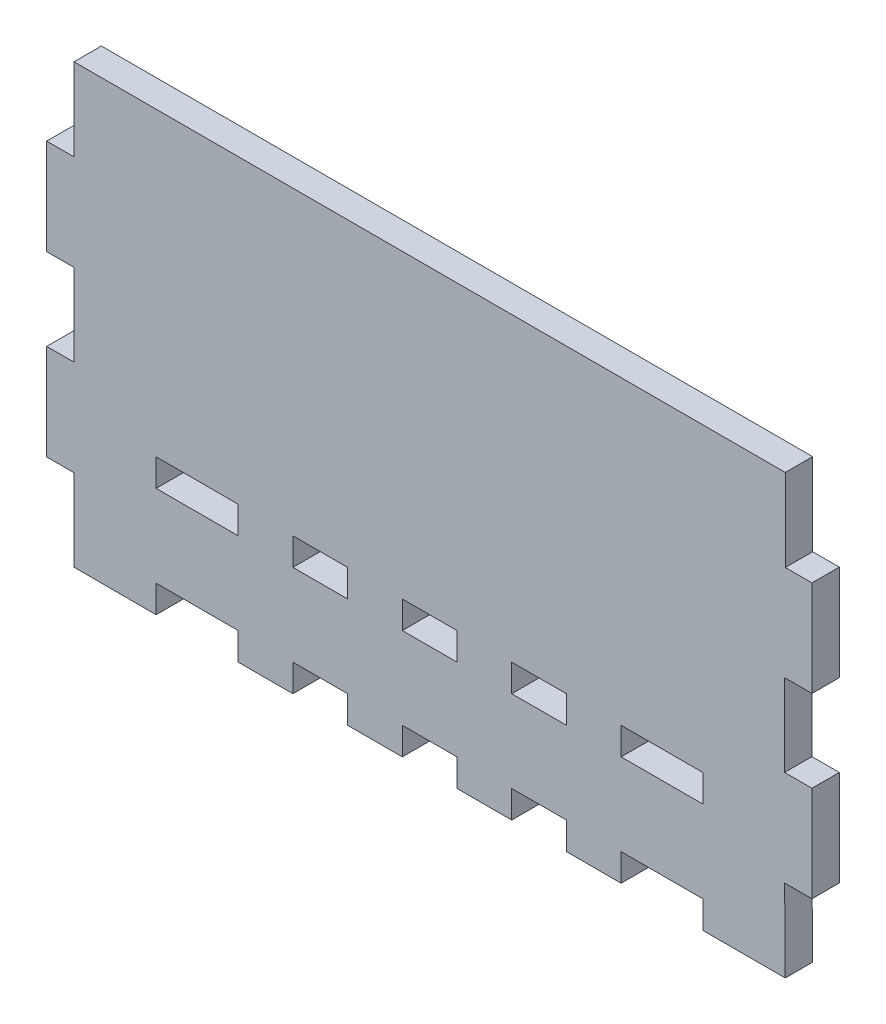
SolidWorks part; units mm, degrees
ref_plane "Front Plane" through (0, 0, 0) normal (0, 0, 1) x (1, 0, 0)
ref_plane "Top Plane" through (0, 0, 0) normal (0, 1, 0) x (1, 0, 0)
ref_plane "Right Plane" through (0, 0, 0) normal (1, 0, 0) x (0, 0, -1)
sketch "Sketch1" plane through (0, 0, 0) normal (0, 0, 1) x (1, 0, 0)
  line L0 (64.6909, 24.8977) -> (64.6909, 39.9469)
  line L1 (-70.3091, 24.8977) -> (-70.3091, 7.3977)
  line L2 (64.5658, 7.3977) -> (64.5658, -7.6023)
  line L3 (-70.3091, -7.6023) -> (-70.3091, -25.1023)
  line L4 (64.5658, -25.1023) -> (64.6848, -40.0793)
  line L5 (-5.3091, -35.0793) -> (-5.3091, -40.0793)
  line L6 (-5.3091, -35.0793) -> (4.6909, -35.0793)
  line L7 (-65.3091, 24.8977) -> (-65.3091, 39.9469)
  line L8 (4.6909, -35.0793) -> (4.6909, -40.0793)
  line L9 (-65.3091, 39.9469) -> (64.6909, 39.9469)
  line L10 (-15.3091, -35.0793) -> (-15.3091, -40.0793)
  line L11 (-65.3091, 7.3977) -> (-65.3091, -7.6023)
  line L12 (-70.3091, 24.8977) -> (-65.3091, 24.8977)
  line L13 (-70.3091, 7.3977) -> (-65.3091, 7.3977)
  line L14 (-70.3091, -7.6023) -> (-65.3091, -7.6023)
  line L15 (-70.3091, -25.1023) -> (-65.3091, -25.1023)
  line L16 (-65.3091, -25.1023) -> (-65.3091, -40.0531)
  line L17 (49.6848, -40.0793) -> (64.6848, -40.0793)
  line L18 (-35.3091, -40.0793) -> (-25.3091, -40.0793)
  line L19 (64.6909, 24.8977) -> (69.5658, 24.8977)
  line L20 (64.5658, 7.3977) -> (69.5658, 7.3977)
  line L21 (69.5658, 24.8977) -> (69.5658, 7.3977)
  line L22 (64.5658, -7.6023) -> (69.5658, -7.6023)
  line L23 (64.5658, -25.1023) -> (69.5658, -25.1023)
  line L24 (69.5658, -7.6023) -> (69.5658, -25.1023)
  line L25 (-50.3091, -35.0793) -> (-35.3091, -35.0793)
  line L26 (-65.3091, -40.0531) -> (-50.3091, -40.0793)
  line L27 (-50.3091, -40.0793) -> (-50.3091, -35.0793)
  line L28 (49.6848, -40.0793) -> (49.6848, -35.0793)
  line L29 (34.6909, -35.0793) -> (49.6848, -35.0793)
  line L30 (-35.3091, -35.0793) -> (-35.3091, -40.0793)
  line L31 (-25.3091, -35.0793) -> (-15.3091, -35.0793)
  line L32 (-25.3091, -35.0793) -> (-25.3091, -40.0793)
  line L33 (-15.3091, -40.0793) -> (-5.3091, -40.0793)
  line L34 (4.6909, -40.0793) -> (14.6909, -40.0793)
  line L35 (14.6909, -35.0793) -> (24.6909, -35.0793)
  line L36 (14.6909, -35.0793) -> (14.6909, -40.0793)
  line L37 (24.6909, -35.0793) -> (24.6909, -40.0793)
  line L38 (24.6909, -40.0793) -> (34.6909, -40.0793)
  line L39 (34.6909, -35.0793) -> (34.6909, -40.0793)
  line L40 (-5.3091, -15.0793) -> (-5.3091, -20.0793)
  line L41 (-5.3091, -15.0793) -> (4.6909, -15.0793)
  line L42 (4.6909, -15.0793) -> (4.6909, -20.0793)
  line L43 (-15.3091, -15.0793) -> (-15.3091, -20.0793)
  line L44 (-50.3091, -15.0793) -> (-35.3091, -15.0793)
  line L45 (-50.3091, -20.0793) -> (-50.3091, -15.0793)
  line L46 (49.6848, -20.0793) -> (49.6848, -15.0793)
  line L47 (34.6909, -15.0793) -> (49.6848, -15.0793)
  line L48 (-35.3091, -15.0793) -> (-35.3091, -20.0793)
  line L49 (-25.3091, -15.0793) -> (-15.3091, -15.0793)
  line L50 (-25.3091, -15.0793) -> (-25.3091, -20.0793)
  line L51 (14.6909, -15.0793) -> (24.6909, -15.0793)
  line L52 (14.6909, -15.0793) -> (14.6909, -20.0793)
  line L53 (24.6909, -15.0793) -> (24.6909, -20.0793)
  line L54 (34.6909, -15.0793) -> (34.6909, -20.0793)
  line L57 (-50.3091, -20.0793) -> (-35.3091, -20.0793)
  line L58 (-25.3091, -20.0793) -> (-15.3091, -20.0793)
  line L59 (-5.3091, -20.0793) -> (4.6909, -20.0793)
  line L60 (14.6909, -20.0793) -> (24.6909, -20.0793)
  line L61 (34.6909, -20.0793) -> (49.6848, -20.0793)
  line L63 (-70.3091, 12.3977) -> (-70.3091, -5.1023) [skipped]
  line L64 (-65.3091, 59.9469) -> (64.6909, 59.9469) [skipped]
  dimension "D1" = 130
  dimension "D2" = 75.0262
  dimension "D3" = 2
  dimension "D4" = 15
extrude "Boss-Extrude2" add sketch "Sketch1" along normal blind 5
